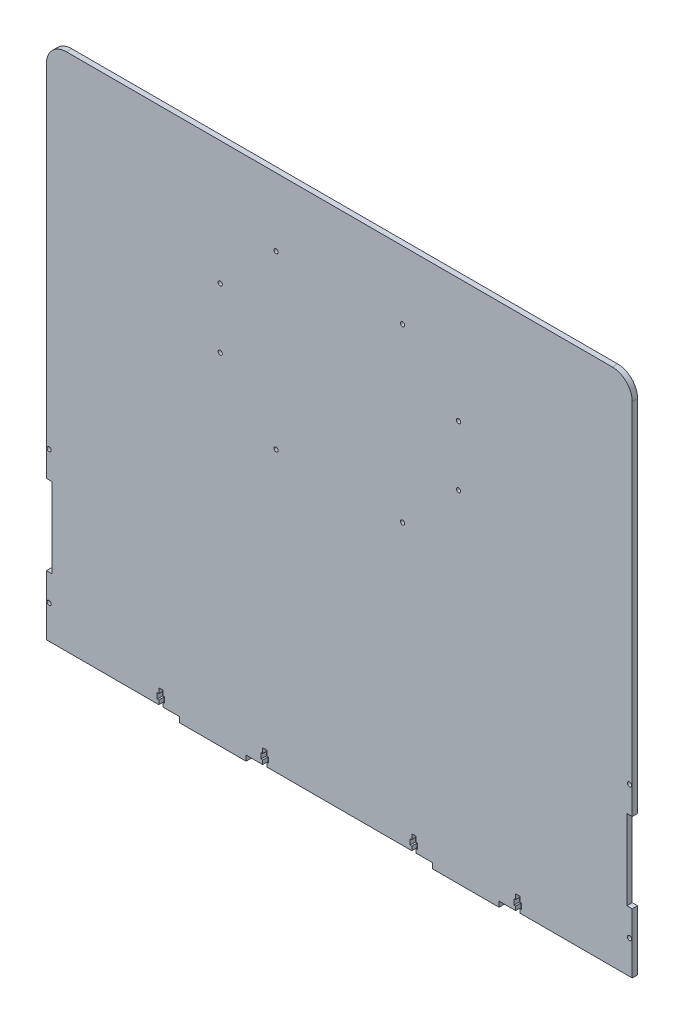
SolidWorks part; units mm, degrees
ref_plane "Plan de face" through (0, 0, 0) normal (0, 0, 1) x (1, 0, 0)
ref_plane "Plan de dessus" through (0, 0, 0) normal (0, 1, 0) x (1, 0, 0)
ref_plane "Plan de droite" through (0, 0, 0) normal (1, 0, 0) x (0, 0, -1)
sketch "Esquisse1" plane through (0, 0, 0) normal (0, 0, 1) x (1, 0, 0)
  line L1 (220, -195) -> (-220, -195)
  line L2 (220, -195) -> (220, 195)
  line L3 (220, 195) -> (-220, 195)
  line L4 (-220, -195) -> (-220, 195)
  line L5 (220, -195) -> (-220, 195) construction
  line L6 (220, 195) -> (-220, -195) construction
  point P1 (0, 0)
  dimension "D1" = 440
  dimension "D2" = 390
extrude "Boss.-Extru.1" add sketch "Esquisse1" along normal blind 4
sketch "Esquisse2" plane through (0, 0, 0) normal (0, 0, -1) x (-1, 0, 0)
  line L0 (220, -195) -> (-220, -195) construction
  line L1 (-120, -195) -> (-70, -195)
  line L2 (-120, -195) -> (-120, -199)
  line L3 (-120, -199) -> (-70, -199)
  line L4 (-70, -195) -> (-70, -199)
  line L5 (220, -199) -> (120, -199) construction
  line L6 (220, -199) -> (220, -195) construction
  line L7 (70, -195) -> (120, -195)
  line L8 (70, -195) -> (70, -199)
  line L9 (70, -199) -> (120, -199)
  line L10 (120, -195) -> (120, -199)
  line L11 (-220, -199) -> (-220, -195) construction
  dimension "D1" = 50
  dimension "D2" = 50
  dimension "D3" = 100
  dimension "D4" = 100
extrude "Boss.-Extru.2" add sketch "Esquisse2" against normal blind 4
sketch "Esquisse3" plane through (0, 0, 0) normal (0, 0, -1) x (-1, 0, 0)
  line L0 (-220, -195) -> (-220, 195) construction
  line L1 (-216, -90) -> (-220, -90)
  line L2 (-216, -90) -> (-216, -150)
  line L3 (-216, -150) -> (-220, -150)
  line L4 (-220, -90) -> (-220, -150)
  line L5 (-220, -150) -> (-216, -150) construction
  line L6 (220, 195) -> (220, -195) construction
  line L7 (216, -90) -> (220, -90)
  line L8 (216, -90) -> (216, -150)
  line L9 (216, -150) -> (220, -150)
  line L10 (220, -90) -> (220, -150)
  line L11 (216, -150) -> (220, -150) construction
extrude "Enlèv. mat.-Extru.1" cut sketch "Esquisse3" against normal blind 4
fillet "Congé1" radius 15 2 edges at (220, 195, 2) (-220, 195, 2)
sketch "Esquisse4" plane through (0, 0, 0) normal (0, 0, -1) x (-1, 0, 0)
  line L0 (220, -150) -> (220, -195) construction
  line L1 (216, -150) -> (220, -150) construction
  line L2 (220, 180) -> (220, -90) construction
  line L3 (220, -90) -> (216, -90) construction
  line L4 (0, 47.1012) -> (0, -53.2131) construction
  line L5 (-131.15, -192) -> (-132.4, -192) construction
  line L6 (-135.6, -184) -> (-132.4, -184) construction
  line L7 (-132.4, -184) -> (-132.4, -187.8) construction
  line L8 (-135.6, -187.8) -> (-135.6, -184) construction
  line L9 (-136.85, -187.8) -> (-135.6, -187.8) construction
  line L10 (-132.4, -187.8) -> (-131.15, -187.8) construction
  line L11 (-131.15, -187.8) -> (-131.15, -192) construction
  line L12 (-136.85, -192) -> (-136.85, -187.8) construction
  line L13 (-135.6, -192) -> (-136.85, -192) construction
  line L15 (-135.6, -195) -> (-135.6, -192) construction
  line L16 (-132.4, -192) -> (-132.4, -195) construction
  line L17 (-57.6, -184) -> (-54.4, -184) construction
  line L18 (-54.4, -184) -> (-54.4, -187.8) construction
  line L19 (-57.6, -187.8) -> (-57.6, -184) construction
  line L20 (-58.85, -187.8) -> (-57.6, -187.8) construction
  line L21 (-54.4, -187.8) -> (-53.15, -187.8) construction
  line L22 (-53.15, -187.8) -> (-53.15, -192) construction
  line L23 (-58.85, -192) -> (-58.85, -187.8) construction
  line L24 (-57.6, -192) -> (-58.85, -192) construction
  line L25 (-53.15, -192) -> (-54.4, -192) construction
  line L26 (-54.4, -192) -> (-54.4, -195) construction
  line L27 (-57.6, -195) -> (-57.6, -192) construction
  line L28 (-57.6, -195) -> (-57.6, -192)
  line L29 (-54.4, -192) -> (-54.4, -195)
  line L30 (-53.15, -192) -> (-54.4, -192)
  line L31 (-57.6, -192) -> (-58.85, -192)
  line L32 (-58.85, -192) -> (-58.85, -187.8)
  line L33 (-53.15, -187.8) -> (-53.15, -192)
  line L34 (-54.4, -187.8) -> (-53.15, -187.8)
  line L35 (-58.85, -187.8) -> (-57.6, -187.8)
  line L36 (-57.6, -187.8) -> (-57.6, -184)
  line L37 (-54.4, -184) -> (-54.4, -187.8)
  line L38 (-57.6, -184) -> (-54.4, -184)
  line L39 (-132.4, -192) -> (-132.4, -195)
  line L40 (-135.6, -195) -> (-135.6, -192)
  line L41 (-131.15, -192) -> (-132.4, -192)
  line L42 (-135.6, -192) -> (-136.85, -192)
  line L43 (-136.85, -192) -> (-136.85, -187.8)
  line L44 (-131.15, -187.8) -> (-131.15, -192)
  line L45 (-132.4, -187.8) -> (-131.15, -187.8)
  line L46 (-136.85, -187.8) -> (-135.6, -187.8)
  line L47 (-135.6, -187.8) -> (-135.6, -184)
  line L48 (-132.4, -184) -> (-132.4, -187.8)
  line L49 (-135.6, -184) -> (-132.4, -184)
  line L50 (135.6, -184) -> (132.4, -184)
  line L51 (132.4, -184) -> (132.4, -187.8)
  line L52 (135.6, -187.8) -> (135.6, -184)
  line L53 (136.85, -187.8) -> (135.6, -187.8)
  line L54 (132.4, -187.8) -> (131.15, -187.8)
  line L55 (131.15, -187.8) -> (131.15, -192)
  line L56 (136.85, -192) -> (136.85, -187.8)
  line L57 (135.6, -192) -> (136.85, -192)
  line L58 (131.15, -192) -> (132.4, -192)
  line L59 (135.6, -195) -> (135.6, -192)
  line L60 (132.4, -192) -> (132.4, -195)
  line L61 (57.6, -184) -> (54.4, -184)
  line L62 (54.4, -184) -> (54.4, -187.8)
  line L63 (57.6, -187.8) -> (57.6, -184)
  line L64 (58.85, -187.8) -> (57.6, -187.8)
  line L65 (54.4, -187.8) -> (53.15, -187.8)
  line L66 (53.15, -187.8) -> (53.15, -192)
  line L67 (58.85, -192) -> (58.85, -187.8)
  line L68 (57.6, -192) -> (58.85, -192)
  line L69 (53.15, -192) -> (54.4, -192)
  line L70 (54.4, -192) -> (54.4, -195)
  line L71 (57.6, -195) -> (57.6, -192)
  circle A0 centre (218, -170) radius 1.6
  circle A1 centre (218, -70) radius 1.6
  circle A2 centre (-218, -70) radius 1.6
  circle A3 centre (-218, -170) radius 1.6
  line M10 (-220, -195) -> (-120, -195)
  line M14 (-70, -195) -> (70, -195)
  line M18 (120, -195) -> (220, -195)
  dimension "D1" = 3.2
  dimension "D2" = 2
  dimension "D3" = 20
  dimension "D4" = 3.2
  dimension "D5" = 2
  dimension "D6" = 20
extrude "Enlèv. mat.-Extru.2" cut sketch "Esquisse4" against normal blind 10 contours L49 L47 L46 L43 L42 L40 L39 L41 L44 L45 L48 M10 | L38 L36 L35 L32 L31 L28 L29 L30 L33 L34 L37 M14 | A3 | A2 | A1 | A0 | L71 L68 L67 L64 L63 L61 L62 L65 L66 L69 L70 M14 | L58 L60 L59 L57 L56 L53 L52 L50 L51 L54 L55 M18
sketch "Esquisse5" plane through (0, 0, 0) normal (0, 0, -1) x (-1, 0, 0)
  circle A1 centre (-47.5, 144.0409) radius 1.6
  circle A2 centre (-47.5, 144.0409) radius 1.6
  circle A3 centre (-89.5, 102.0409) radius 1.6
  circle A4 centre (-89.5, 102.0409) radius 1.6
  circle A5 centre (-89.5, 57.0409) radius 1.6
  circle A6 centre (-89.5, 57.0409) radius 1.6
  circle A7 centre (-47.5, 15.0409) radius 1.6
  circle A8 centre (-47.5, 15.0409) radius 1.6
  circle A9 centre (89.5, 57.0409) radius 1.6
  circle A10 centre (89.5, 57.0409) radius 1.6
  circle A11 centre (47.5, 15.0409) radius 1.6
  circle A12 centre (47.5, 15.0409) radius 1.6
  circle A13 centre (47.5, 144.0409) radius 1.6
  circle A14 centre (47.5, 144.0409) radius 1.6
  circle A15 centre (89.5, 102.0409) radius 1.6
  circle A16 centre (89.5, 102.0409) radius 1.6
  dimension "D1" = 0
  dimension "D2" = 0
  dimension "D3" = 0
  dimension "D4" = 0
  dimension "D5" = 0
  dimension "D6" = 0
  dimension "D7" = 0
  dimension "D8" = 0
extrude "Enlèv. mat.-Extru.3" cut sketch "Esquisse5" against normal blind 4
